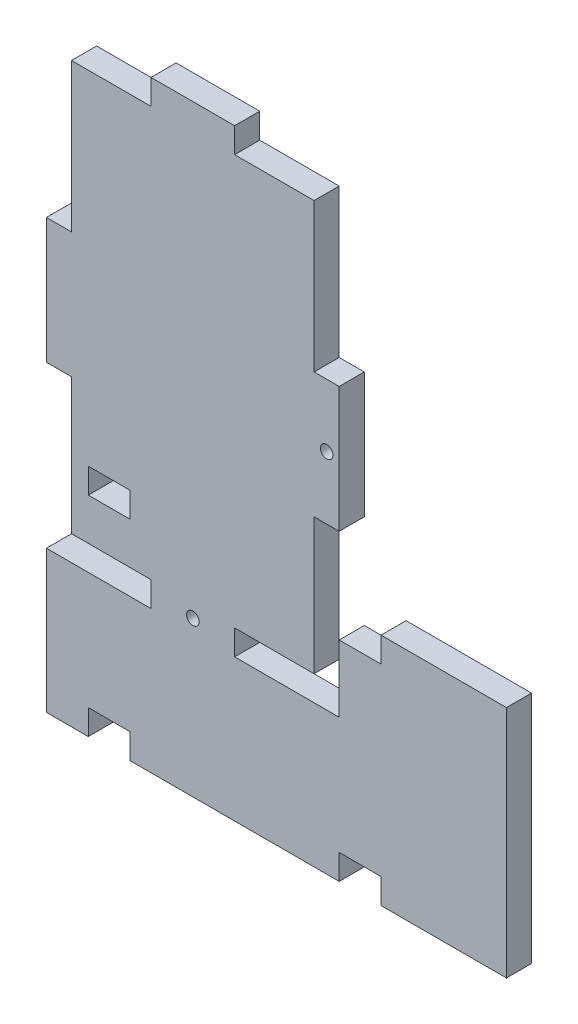
SolidWorks part; units mm, degrees
ref_plane "Plan de face" through (0, 0, 0) normal (0, 0, 1) x (1, 0, 0)
ref_plane "Plan de dessus" through (0, 0, 0) normal (0, 1, 0) x (1, 0, 0)
ref_plane "Plan de droite" through (0, 0, 0) normal (1, 0, 0) x (0, 0, -1)
sketch "Esquisse1" plane through (0, 0, 0) normal (0, 0, 1) x (1, 0, 0)
  line L1 (0, 0) -> (-110, 0)
  line L2 (0, 0) -> (0, 144)
  line L3 (0, 144) -> (-110, 144)
  line L4 (-110, 0) -> (-110, 144)
  dimension "D1" = 144
  dimension "D2" = 110
extrude "Boss.-Extru.1" add sketch "Esquisse1" along normal blind 6
sketch "Esquisse2" plane through (0, 0, 0) normal (0, 0, -1) x (-1, 0, 0)
  line L0 (0, 144) -> (110, 144) construction
  line L1 (40, 102.5) -> (40, 72.5)
  line L3 (46, 138) -> (65, 138)
  line L4 (65, 144) -> (65, 138)
  line L5 (110, 144) -> (85, 144)
  line L6 (110, 72.5) -> (110, 34)
  line L7 (104, 138) -> (85, 138)
  line L8 (85, 144) -> (85, 138)
  line L9 (110, 144) -> (110, 0) construction
  line L11 (110, 144) -> (110, 102.5)
  line L12 (40, 50) -> (40, 34)
  line L13 (104, 40) -> (104, 72.5)
  line L14 (110, 0) -> (0, 0) construction
  line L15 (110, 34) -> (85, 34)
  line L16 (65, 144) -> (0, 144)
  line L17 (104, 40) -> (85, 40)
  line L18 (85, 34) -> (85, 40)
  line L19 (65, 40) -> (46, 40)
  line L20 (65, 40) -> (65, 34)
  line L21 (65, 34) -> (40, 34)
  line L22 (0, 144) -> (0, 56)
  line L23 (0, 0) -> (0, 144) construction
  line L24 (0, 56) -> (30, 56)
  line L25 (40, 102.5) -> (46, 102.5)
  line L26 (46, 138) -> (46, 102.5)
  line L29 (110, 72.5) -> (104, 72.5)
  line L30 (40, 72.5) -> (46, 72.5)
  line L31 (46, 40) -> (46, 72.5)
  line L32 (100, 0) -> (90, 0)
  line L33 (110, 102.5) -> (104, 102.5)
  line L34 (104, 138) -> (104, 102.5)
  line L35 (100, 0) -> (100, 6)
  line L36 (100, 6) -> (90, 6)
  line L37 (90, 0) -> (90, 6)
  line L39 (40, 0) -> (30, 0)
  line L40 (40, 0) -> (40, 6)
  line L41 (40, 6) -> (30, 6)
  line L42 (30, 0) -> (30, 6)
  line L43 (100, 56) -> (90, 56)
  line L44 (100, 56) -> (100, 50)
  line L45 (100, 50) -> (90, 50)
  line L46 (90, 56) -> (90, 50)
  line L47 (30, 50) -> (40, 50)
  line L48 (30, 50) -> (30, 56)
  dimension "D2" = 20
  dimension "D3" = 6
  dimension "D4" = 25
  dimension "D5" = 6
  dimension "D6" = 35.5
  dimension "D7" = 38.5
  dimension "D8" = 25
  dimension "D9" = 6
  dimension "D10" = 6
  dimension "D11" = 41.5
  dimension "D12" = 20
  dimension "D13" = 30
  dimension "D14" = 25
  dimension "D15" = 30
  dimension "D16" = 6
  dimension "D17" = 6
  dimension "D18" = 6
  dimension "D19" = 38.5
  dimension "D20" = 6
  dimension "D21" = 10
  dimension "D22" = 10
  dimension "D23" = 10
  dimension "D24" = 50
  dimension "D25" = 6
  dimension "D26" = 6
  dimension "D27" = 10
  dimension "D28" = 10
  dimension "D29" = 44
  dimension "D30" = 6
  dimension "D31" = 64
  dimension "D32" = 10
  dimension "D33" = 6
  dimension "D34" = 16.5
extrude "Enlèv. mat.-Extru.1" cut sketch "Esquisse2" against normal through all
sketch "Esquisse3" plane through (0, 0, 0) normal (0, 0, -1) x (-1, 0, 0)
  line L0 (40, 72.5) -> (40, 102.5) construction
  line L1 (46, 72.5) -> (40, 72.5) construction
  line L2 (85, 40) -> (85, 34) construction
  line L3 (104, 40) -> (85, 40) construction
  circle A0 centre (43, 87.5) radius 1.5
  circle A1 centre (75, 37) radius 1.5
  dimension "D1" = 3
  dimension "D2" = 3
  dimension "D3" = 15
  dimension "D4" = 3
  dimension "D5" = 10
  dimension "D6" = 3
extrude "Enlèv. mat.-Extru.2" cut sketch "Esquisse3" against normal through all
sketch "Esquisse4" plane through (0, 0, 0) normal (0, 0, -1) x (-1, 0, 0)
  circle A0 centre (43, 87.5) radius 2.995
  circle A1 centre (75, 37) radius 3
  dimension "D1" = 5.99
  dimension "D2" = 6
extrude "Enlèv. mat.-Extru.3" cut sketch "Esquisse4" against normal blind 3
